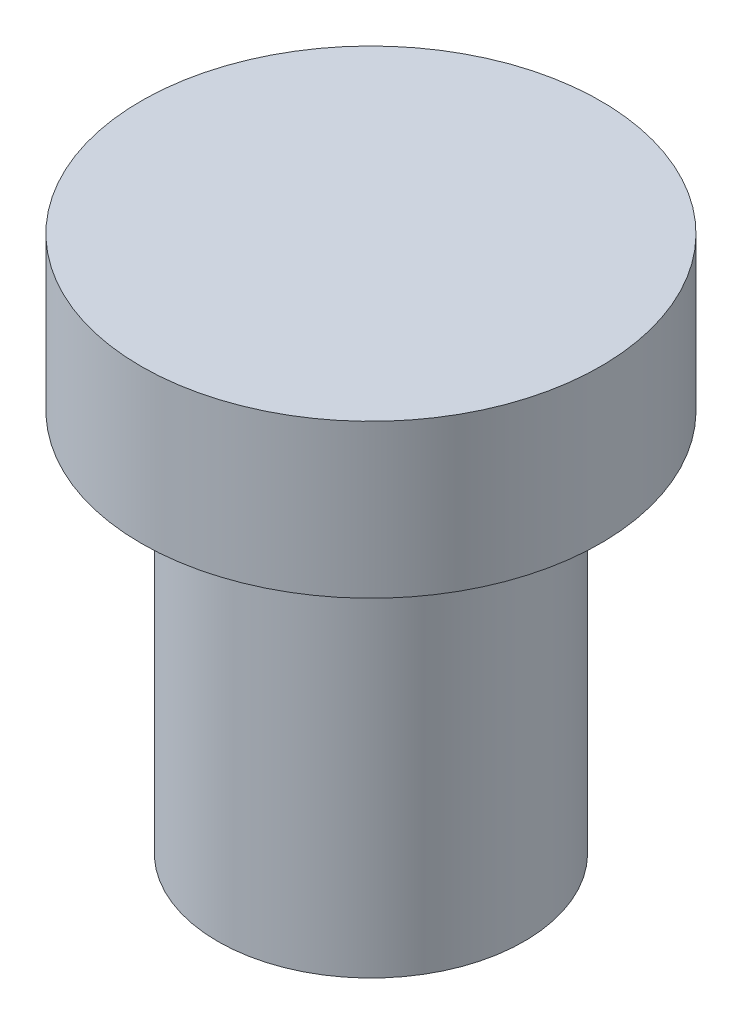
SolidWorks part; units mm, degrees
material "3.0205 (EN-AW 1200)"
ref_plane "정면" through (0, 0, 0) normal (0, 0, 1) x (1, 0, 0)
ref_plane "윗면" through (0, 0, 0) normal (0, 1, 0) x (1, 0, 0)
ref_plane "우측면" through (0, 0, 0) normal (1, 0, 0) x (0, 0, -1)
sketch "스케치1" plane through (0, 0, 0) normal (1, 0, 0) x (0, 0, -1)
  line L0 (0, 20.9905) -> (0, -20.0677) construction
  line L1 (0, 16.2462) -> (3, 16.2462)
  line L2 (3, 16.2462) -> (3, 14.2462)
  line L3 (3, 14.2462) -> (2, 14.2462)
  line L4 (2, 14.2462) -> (2, 9.2462)
  line L5 (2, 9.2462) -> (0, 9.2462)
  line L6 (0, 16.2462) -> (0, 9.2462)
  dimension "D1" = 5
  dimension "D2" = 2
  dimension "D3" = 3
  dimension "D4" = 2
revolve "회전1" add sketch "스케치1" angle 360 about L0
